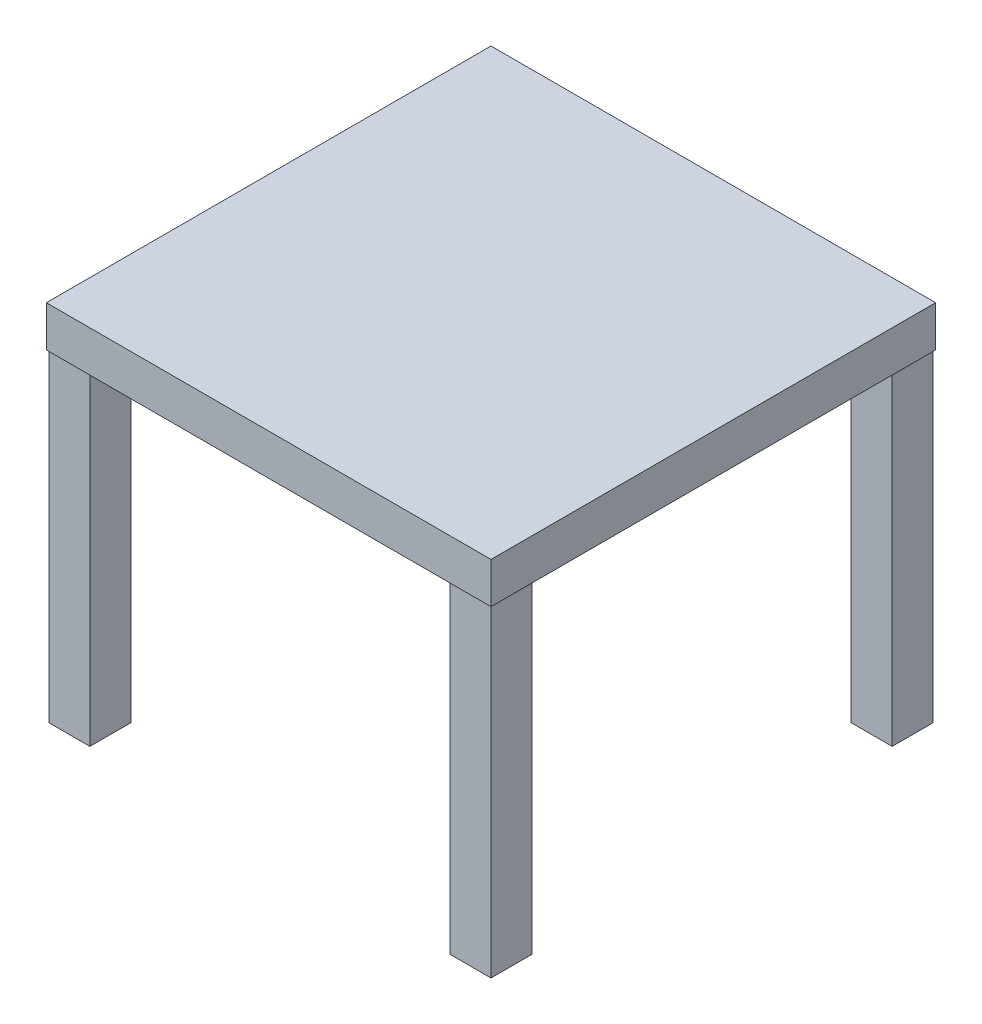
SolidWorks part; units mm, degrees
ref_plane "Front Plane" through (0, 0, 0) normal (0, 0, 1) x (1, 0, 0)
ref_plane "Top Plane" through (0, 0, 0) normal (0, 1, 0) x (1, 0, 0)
ref_plane "Right Plane" through (0, 0, 0) normal (1, 0, 0) x (0, 0, -1)
sketch "Sketch1" plane through (0, 0, 0) normal (0, 1, 0) x (1, 0, 0)
  line L0 (-275, 275) -> (275, -275) construction
  line L1 (-275, 275) -> (275, 275)
  line L2 (-275, 275) -> (-275, -275)
  line L3 (-275, -275) -> (275, -275)
  line L4 (275, 275) -> (275, -275)
  dimension "D1" = 550
  dimension "D2" = 550
extrude "Boss-Extrude1" add sketch "Sketch1" along normal blind 50.6
sketch "Sketch3" plane through (0, 0, 0) normal (0, -1, 0) x (1, 0, 0)
  line L0 (275, 275) -> (275, -275) construction
  line L1 (273.4, -273.4) -> (222.8, -273.4)
  line L2 (273.4, -273.4) -> (273.4, -222.8)
  line L3 (273.4, -222.8) -> (222.8, -222.8)
  line L4 (222.8, -273.4) -> (222.8, -222.8)
  line L5 (-273.4, -273.4) -> (-222.8, -273.4)
  line L6 (-273.4, -273.4) -> (-273.4, -222.8)
  line L7 (-273.4, -222.8) -> (-222.8, -222.8)
  line L8 (-222.8, -273.4) -> (-222.8, -222.8)
  line L9 (-273.4, 273.4) -> (-222.8, 273.4)
  line L10 (-273.4, 273.4) -> (-273.4, 222.8)
  line L11 (-273.4, 222.8) -> (-222.8, 222.8)
  line L12 (-222.8, 273.4) -> (-222.8, 222.8)
  line L13 (222.8, 222.8) -> (273.4, 222.8)
  line L14 (222.8, 222.8) -> (222.8, 273.4)
  line L15 (222.8, 273.4) -> (273.4, 273.4)
  line L16 (273.4, 222.8) -> (273.4, 273.4)
  line L17 (275, -275) -> (-275, -275) construction
  line L18 (-275, 275) -> (275, 275) construction
  line L19 (-275, -275) -> (-275, 275) construction
  point P16 (87.9393, 160.1228)
  point P17 (74.0156, 141.0693)
  point P18 (69.6186, -80.9775)
  point P27 (-35.8533, -45.0689)
  point P28 (153.8938, -138.138)
  dimension "D1" = 1.6
  dimension "D2" = 1.6
  dimension "D3" = 1.6
  dimension "D4" = 1.6
  dimension "D5" = 50.6
extrude "Boss-Extrude2" add sketch "Sketch3" along normal blind 399.4
